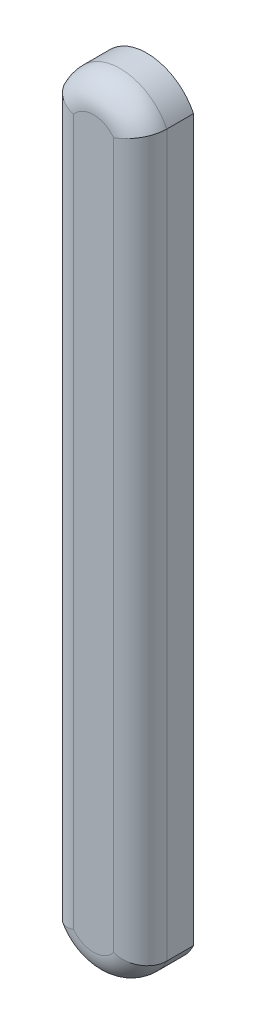
SolidWorks part; units mm, degrees
material "Plastique personnalisé"
ref_plane "Plan de face" through (0, 0, 0) normal (0, 0, 1) x (1, 0, 0)
ref_plane "Plan de dessus" through (0, 0, 0) normal (0, 1, 0) x (1, 0, 0)
ref_plane "Plan de droite" through (0, 0, 0) normal (1, 0, 0) x (0, 0, -1)
sketch "Esquisse1" plane through (0, 0, 0) normal (0, 0, 1) x (1, 0, 0)
  line L0 (0, 1.35) -> (0.35, 1.35) construction
  line L2 (0, 0) -> (0, 2.7)
  line L4 (0.35, 0) -> (0.35, 2.7)
  arc A0 (0, 2.7) -> (0.35, 2.7) centre (0.175, 2.614) cw
  arc A1 (0, 0) -> (0.35, 0) centre (0.175, 0.086) ccw
  dimension "D1" = 2.7
  dimension "D2" = 0.35
  dimension "D3" = 2.7
extrude "Boss.-Extru.1" add sketch "Esquisse1" along normal blind 0.2
fillet "Congé1" radius 0.1 4 edges at (0.175, -0.109, 0.2) (0, 1.35, 0.2) (0.35, 1.35, 0.2) (0.175, 2.809, 0.2)
